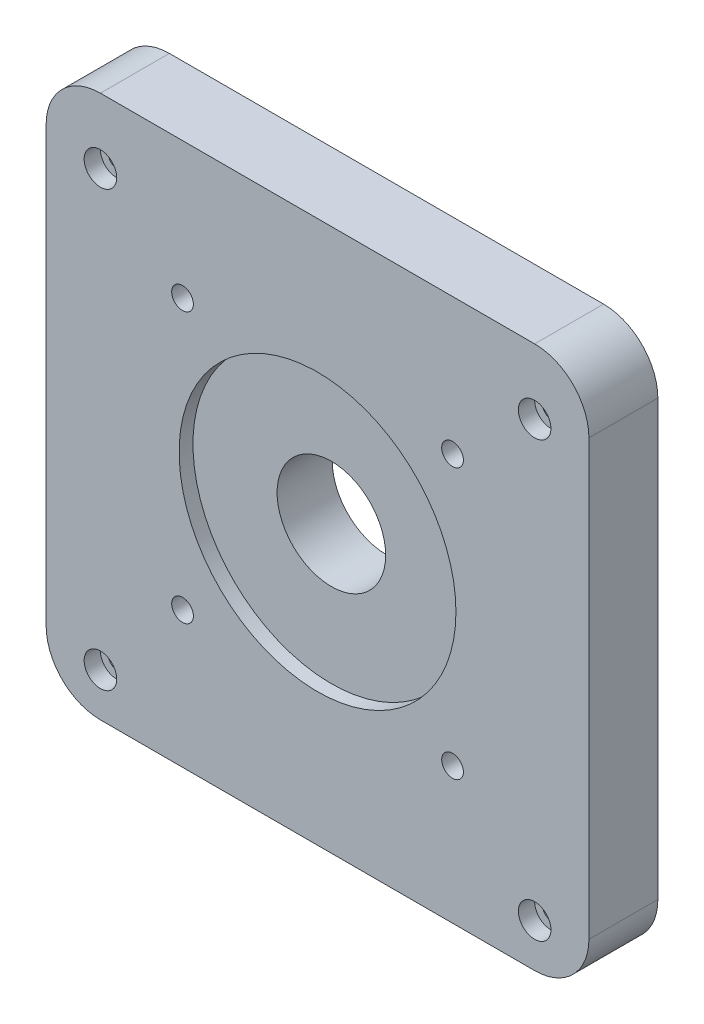
SolidWorks part; units mm, degrees
ref_plane "Front Plane" through (0, 0, 0) normal (0, 0, 1) x (1, 0, 0)
ref_plane "Top Plane" through (0, 0, 0) normal (0, 1, 0) x (1, 0, 0)
ref_plane "Right Plane" through (0, 0, 0) normal (1, 0, 0) x (0, 0, -1)
sketch "Croquis1" plane through (0, 0, 0) normal (0, 0, 1) x (1, 0, 0)
  line L1 (10, 0) -> (90, 0)
  line L2 (0, 10) -> (0, 90)
  line L3 (10, 100) -> (90, 100)
  line L4 (100, 10) -> (100, 90)
  arc A0 (90, 100) -> (100, 90) centre (90, 90) cw
  arc A1 (90, 0) -> (100, 10) centre (90, 10) ccw
  arc A2 (10, 0) -> (0, 10) centre (10, 10) cw
  arc A3 (0, 90) -> (10, 100) centre (10, 90) cw
  point P11 (0, 0)
  dimension "D1" = 10
extrude "Saliente-Extruir1" add sketch "Croquis1" along normal blind 12.7
sketch "Croquis2" plane through (0, 0, 12.7) normal (0, 0, 1) x (1, 0, 0)
  line L0 (0, 90) -> (0, 10) construction
  line L3 (100, 10) -> (100, 90) construction
  circle A0 centre (10, 88) radius 3
  circle A1 centre (10, 8) radius 3
  circle A2 centre (90, 88) radius 3
  circle A3 centre (90, 8) radius 3
  point P10 (50, 50)
  dimension "D1" = 10
  dimension "D2" = 10
  dimension "D3" = 80
  dimension "D4" = 80
  dimension "D5" = 10
  dimension "D6" = 42
  dimension "D7" = 10
  dimension "D8" = 42
extrude "Cortar-Extruir1" cut sketch "Croquis2" against normal blind 3
sketch "Croquis3" plane through (0, 0, 12.7) normal (0, 0, 1) x (1, 0, 0)
  line L1 (90, 100) -> (10, 100) construction
  line L2 (100, 10) -> (100, 90) construction
  circle A5 centre (50, 50) radius 10
  circle A6 centre (25.125, 74.875) radius 2
  circle A7 centre (74.875, 74.875) radius 2
  circle A8 centre (25.125, 25.125) radius 2
  circle A9 centre (74.875, 25.125) radius 2
  dimension "D1" = 49.75
  dimension "D7" = 50
  dimension "D8" = 50
  dimension "D2" = 0
  dimension "D9" = 49.75
  dimension "D10" = 24.875
  dimension "D11" = 24.875
  dimension "D3" = 49.75
  dimension "D4" = 49.75
  dimension "D5" = 24.875
  dimension "D6" = 24.875
extrude "Cortar-Extruir2" cut sketch "Croquis3" against normal blind 31
sketch "Croquis4" plane through (0, 0, 9.7) normal (0, 0, 1) x (1, 0, 0)
  circle A0 centre (10, 88) radius 1.5
  circle A1 centre (90, 88) radius 1.5
  circle A2 centre (90, 8) radius 1.5
  circle A3 centre (10, 8) radius 1.5
extrude "Cortar-Extruir3" cut sketch "Croquis4" against normal blind 31
sketch "Croquis5" plane through (0, 0, 0) normal (0, 0, -1) x (-1, 0, 0)
  circle A0 centre (-74.875, 74.875) radius 4
  circle A1 centre (-25.125, 74.875) radius 4
  circle A2 centre (-25.125, 25.125) radius 4
  circle A3 centre (-74.875, 25.125) radius 4
extrude "Cortar-Extruir4" cut sketch "Croquis5" against normal blind 3
sketch "Croquis6" plane through (0, 0, 12.7) normal (0, 0, 1) x (1, 0, 0)
  circle A0 centre (50, 50) radius 25.5
extrude "Cortar-Extruir5" cut sketch "Croquis6" against normal blind 2.55
